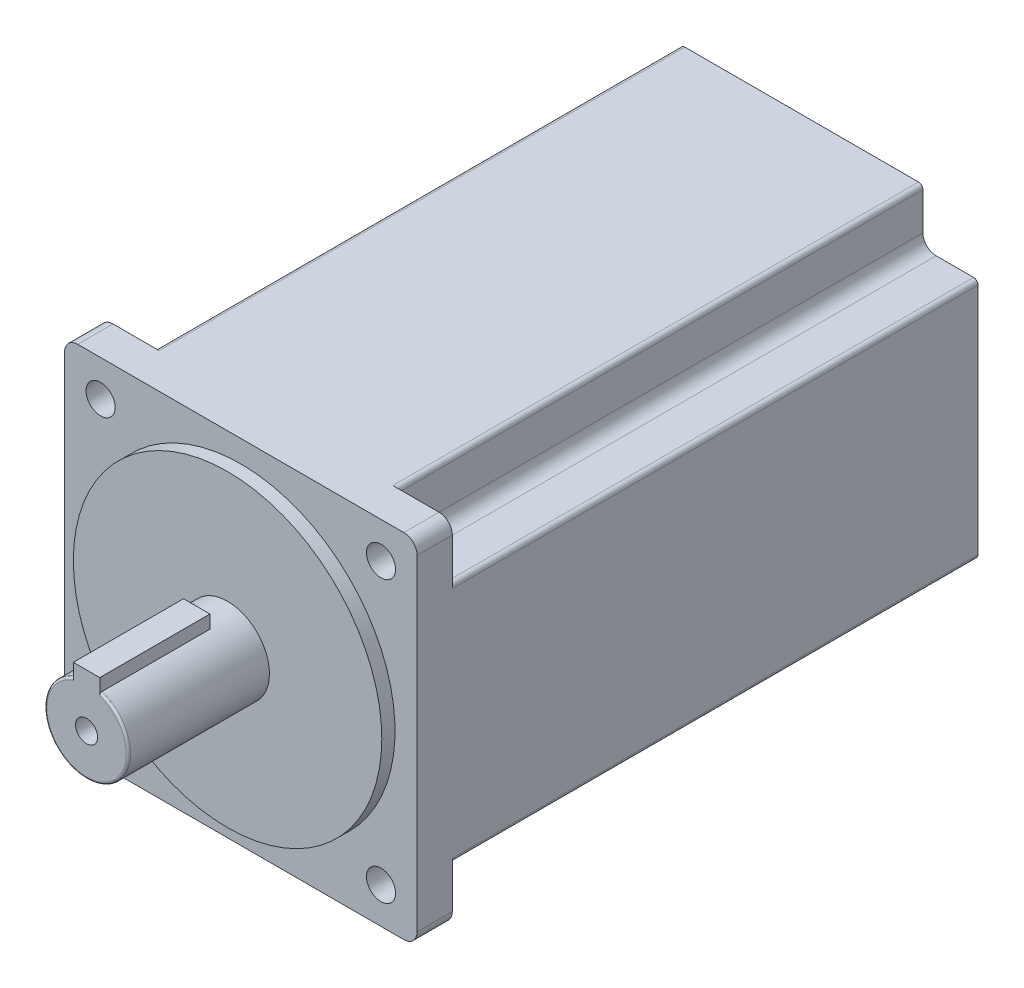
SolidWorks part; units mm, degrees
ref_plane "前视基准面" through (0, 0, 0) normal (0, 0, 1) x (1, 0, 0)
ref_plane "上视基准面" through (0, 0, 0) normal (0, 1, 0) x (1, 0, 0)
ref_plane "右视基准面" through (0, 0, 0) normal (1, 0, 0) x (0, 0, -1)
sketch "草图1" plane through (0, 0, 0) normal (0, 0, 1) x (1, 0, 0)
  line L1 (-40, -40) -> (40, -40)
  line L2 (-40, -40) -> (-40, 40)
  line L3 (-40, 40) -> (40, 40)
  line L4 (40, -40) -> (40, 40)
  line L5 (-40, -40) -> (40, 40) construction
  line L6 (-40, 40) -> (40, -40) construction
  point P0 (0, 0)
  dimension "D1" = 80
  dimension "D2" = 80
extrude "凸台-拉伸1" add sketch "草图1" along normal blind 8
fillet "圆角1" radius 3 4 edges at (40, -40, 4) (-40, -40, 4) (-40, 40, 4) (40, 40, 4)
sketch "草图2" plane through (0, 0, 8) normal (0, 0, 1) x (1, 0, 0)
  line L0 (0, 0) -> (31.8198, 31.8198) construction
  line L1 (0, 0) -> (-31.8198, -31.8198) construction
  line L2 (0, 0) -> (31.8198, -31.8198) construction
  line L3 (0, 0) -> (-31.8198, 31.8198) construction
  line L4 (0, 0) -> (0, 45) construction
  circle A0 centre (0, 0) radius 45 construction
  dimension "D1" = 90
  dimension "D2" = 45
  dimension "D3" = 45
hole_wizard "Ø6.6 (6.6) 直径孔1" positions "草图4" profile "草图3" hole size "Ø6.6" standard "ANSI Metric" end condition through all
sketch "草图4" plane through (0, 0, 8) normal (0, 0, 1) x (1, 0, 0)
  point P0 (31.8198, 31.8198)
  point P3 (31.8198, -31.8198)
  point P6 (-31.8198, -31.8198)
  point P9 (-31.8198, 31.8198)
sketch "草图3" plane through (31.8198, 31.8198, 8) normal (1, 0, 0) x (0, -1, 0)
  line L0 (0, 0) -> (0, 8)
  line L1 (0, 8) -> (3.3, 8)
  line L2 (3.3, 8) -> (3.3, 0)
  line L5 (3.3, 0) -> (0, 0)
  line L11 (0, -6.35) -> (0, 107.95) construction
  dimension "通孔孔直径" = 6.6
  dimension "通孔孔深度" = 8
sketch "草图5" plane through (0, 0, 8) normal (0, 0, 1) x (1, 0, 0)
  circle A0 centre (0, 0) radius 35
  dimension "D1" = 70
extrude "凸台-拉伸2" add sketch "草图5" along normal blind 3
sketch "草图6" plane through (0, 0, 11) normal (0, 0, 1) x (1, 0, 0)
  circle A0 centre (0, 0) radius 9.5
  dimension "D1" = 19
extrude "凸台-拉伸3" add sketch "草图6" along normal blind 32
sketch "草图7" plane through (0, 0, 0) normal (0, 0, -1) x (-1, 0, 0)
  line L0 (-27.5, 40) -> (27.5, 40)
  line L1 (-37, 40) -> (37, 40) construction
  line L2 (27.5, 40) -> (27.5, 27.5)
  line L3 (27.5, 27.5) -> (40, 27.5)
  line L4 (40, 37) -> (40, -37) construction
  line L5 (40, 27.5) -> (40, -27.5)
  line L6 (40, -27.5) -> (27.5, -27.5)
  line L7 (27.5, -27.5) -> (27.5, -40)
  line L8 (37, -40) -> (-37, -40) construction
  line L9 (27.5, -40) -> (-27.5, -40)
  line L10 (-27.5, -40) -> (-27.5, -27.5)
  line L11 (-27.5, -27.5) -> (-40, -27.5)
  line L12 (-40, -37) -> (-40, 37) construction
  line L13 (-40, -27.5) -> (-40, 27.5)
  line L14 (-40, 27.5) -> (-27.5, 27.5)
  line L15 (-27.5, 27.5) -> (-27.5, 40)
  line L16 (0, 0) -> (7.8185, 0) construction
  line L17 (0, 0) -> (0, 6.2956) construction
  dimension "D1" = 55
  dimension "D2" = 55
extrude "凸台-拉伸4" add sketch "草图7" along normal blind 119.3
fillet "圆角2" radius 3 4 edges at (27.5, -27.5, -59.65) (-27.5, -27.5, -59.65) (-27.5, 27.5, -59.65) (27.5, 27.5, -59.65)
fillet "圆角3" radius 1 8 edges
sketch "草图8" plane through (0, 0, 43) normal (0, 0, 1) x (1, 0, 0)
  line L0 (0, 0) -> (0, -5.583) construction
  line L1 (-3, 12) -> (3, 12)
  line L2 (-3, 12) -> (-3, 6)
  line L3 (-3, 6) -> (3, 6)
  line L4 (3, 12) -> (3, 6)
  circle A2 centre (0, 0) radius 9.5 construction
  dimension "D1" = 6
  dimension "D2" = 15.5
  dimension "D3" = 6
extrude "凸台-拉伸5" add sketch "草图8" against normal blind 25
fillet "圆角4" radius 0.5 1 edges at (0, -9.5, 43)
sketch "草图9" plane through (0, 0, 43) normal (0, 0, 1) x (1, 0, 0)
  circle A0 centre (0, 0) radius 2.5
extrude "切除-拉伸1" cut sketch "草图9" against normal blind 10
